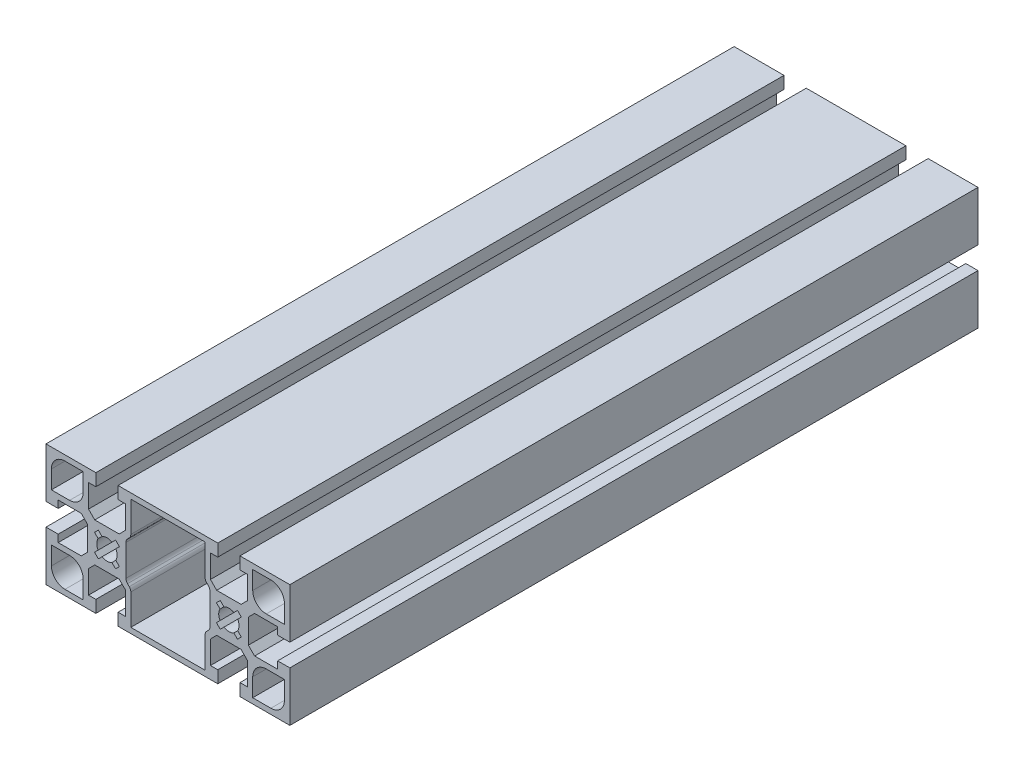
SolidWorks part; units mm, degrees
ref_plane "Front Plane" through (0, 0, 0) normal (0, 0, 1) x (1, 0, 0)
ref_plane "Top Plane" through (0, 0, 0) normal (0, 1, 0) x (1, 0, 0)
ref_plane "Right Plane" through (0, 0, 0) normal (1, 0, 0) x (0, 0, -1)
ref_plane "Plane1" through (0, 0, 0) normal (0, 0, -1) x (-1, 0, 0)
sketch "Sketch1" plane through (0, 0, 0) normal (0, 0, -1) x (-1, 0, 0)
  line L0 (14.9142, -7.1574) -> (14.2858, -7.7858)
  line L1 (13.7, -9.2) -> (13.7, -20.5)
  line L2 (13.7, -20.5) -> (-13.7, -20.5)
  line L3 (-13.7, -20.5) -> (-13.7, -9.2)
  line L4 (-14.2858, -7.7858) -> (-14.9142, -7.1574)
  line L5 (-15.5, -5.7432) -> (-15.5, 5.7432)
  line L6 (-14.9142, 7.1574) -> (-14.2858, 7.7858)
  line L7 (-13.7, 9.2) -> (-13.7, 20.5)
  line L8 (-13.7, 20.5) -> (13.7, 20.5)
  line L9 (13.7, 20.5) -> (13.7, 9.2)
  line L10 (14.2858, 7.7858) -> (14.9142, 7.1574)
  line L11 (15.5, 5.7432) -> (15.5, -5.7432)
  line L12 (43, 15.5) -> (43, 8.8)
  line L13 (43, 8.8) -> (36.3, 8.8)
  line L14 (31.3, 13.8) -> (31.3, 20.5)
  line L15 (31.3, 20.5) -> (38, 20.5)
  line L16 (-36.3, 8.8) -> (-43, 8.8)
  line L17 (-43, 8.8) -> (-43, 15.5)
  line L18 (-38, 20.5) -> (-31.3, 20.5)
  line L19 (-31.3, 20.5) -> (-31.3, 13.8)
  line L20 (-43, -15.5) -> (-43, -8.8)
  line L21 (-43, -8.8) -> (-36.3, -8.8)
  line L22 (-31.3, -13.8) -> (-31.3, -20.5)
  line L23 (-31.3, -20.5) -> (-38, -20.5)
  line L24 (36.3, -8.8) -> (43, -8.8)
  line L25 (43, -8.8) -> (43, -15.5)
  line L26 (38, -20.5) -> (31.3, -20.5)
  line L27 (31.3, -20.5) -> (31.3, -13.8)
  line L28 (-20.6515, 3.2627) -> (-19.318, 4.5962)
  line L29 (-19.318, 4.5962) -> (-17.9038, 3.182)
  line L30 (-17.9038, 3.182) -> (-19.2373, 1.8485)
  line L31 (-19.2373, -1.8485) -> (-17.9038, -3.182)
  line L32 (-17.9038, -3.182) -> (-19.318, -4.5962)
  line L33 (-19.318, -4.5962) -> (-20.6515, -3.2627)
  line L34 (-24.3485, -3.2627) -> (-25.682, -4.5962)
  line L35 (-25.682, -4.5962) -> (-27.0962, -3.182)
  line L36 (-27.0962, -3.182) -> (-25.7627, -1.8485)
  line L37 (-25.7627, 1.8485) -> (-27.0962, 3.182)
  line L38 (-27.0962, 3.182) -> (-25.682, 4.5962)
  line L39 (-25.682, 4.5962) -> (-24.3485, 3.2627)
  line L40 (27.0962, 3.182) -> (25.7627, 1.8485)
  line L41 (25.7627, -1.8485) -> (27.0962, -3.182)
  line L42 (27.0962, -3.182) -> (25.682, -4.5962)
  line L43 (25.682, -4.5962) -> (24.3485, -3.2627)
  line L44 (20.6515, -3.2627) -> (19.318, -4.5962)
  line L45 (19.318, -4.5962) -> (17.9038, -3.182)
  line L46 (17.9038, -3.182) -> (19.2373, -1.8485)
  line L47 (19.2373, 1.8485) -> (17.9038, 3.182)
  line L48 (17.9038, 3.182) -> (19.318, 4.5962)
  line L49 (19.318, 4.5962) -> (20.6515, 3.2627)
  line L50 (24.3485, 3.2627) -> (25.682, 4.5962)
  line L51 (25.682, 4.5962) -> (27.0962, 3.182)
  line L52 (-26.6, 22.5) -> (-45, 22.5)
  line L53 (-45, 22.5) -> (-45, 4.1)
  line L54 (-45, 4.1) -> (-40.5, 4.1)
  line L55 (-40.5, 4.1) -> (-40.5, 6.8)
  line L56 (-40.5, 6.8) -> (-32, 6.8)
  line L57 (-32, 6.8) -> (-29.7, 4.5)
  line L58 (-29.7, 4.5) -> (-29.7, -4.5)
  line L59 (-29.7, -4.5) -> (-32, -6.8)
  line L60 (-32, -6.8) -> (-40.5, -6.8)
  line L61 (-40.5, -6.8) -> (-40.5, -4.1)
  line L62 (-40.5, -4.1) -> (-45, -4.1)
  line L63 (-45, -4.1) -> (-45, -22.5)
  line L64 (-45, -22.5) -> (-26.6, -22.5)
  line L65 (-26.6, -22.5) -> (-26.6, -18)
  line L66 (-26.6, -18) -> (-29.3, -18)
  line L67 (-29.3, -18) -> (-29.3, -9.5)
  line L68 (-29.3, -9.5) -> (-27, -7.2)
  line L69 (-27, -7.2) -> (-18, -7.2)
  line L70 (-18, -7.2) -> (-15.7, -9.5)
  line L71 (-15.7, -9.5) -> (-15.7, -18)
  line L72 (-15.7, -18) -> (-18.4, -18)
  line L73 (-18.4, -18) -> (-18.4, -22.5)
  line L74 (-18.4, -22.5) -> (18.4, -22.5)
  line L75 (18.4, -22.5) -> (18.4, -18)
  line L76 (18.4, -18) -> (15.7, -18)
  line L77 (15.7, -18) -> (15.7, -9.5)
  line L78 (15.7, -9.5) -> (18, -7.2)
  line L79 (18, -7.2) -> (27, -7.2)
  line L80 (27, -7.2) -> (29.3, -9.5)
  line L81 (29.3, -9.5) -> (29.3, -18)
  line L82 (29.3, -18) -> (26.6, -18)
  line L83 (26.6, -18) -> (26.6, -22.5)
  line L84 (26.6, -22.5) -> (45, -22.5)
  line L85 (45, -22.5) -> (45, -4.1)
  line L86 (45, -4.1) -> (40.5, -4.1)
  line L87 (40.5, -4.1) -> (40.5, -6.8)
  line L88 (40.5, -6.8) -> (32, -6.8)
  line L89 (32, -6.8) -> (29.7, -4.5)
  line L90 (29.7, -4.5) -> (29.7, 4.5)
  line L91 (29.7, 4.5) -> (32, 6.8)
  line L92 (32, 6.8) -> (40.5, 6.8)
  line L93 (40.5, 6.8) -> (40.5, 4.1)
  line L94 (40.5, 4.1) -> (45, 4.1)
  line L95 (45, 4.1) -> (45, 22.5)
  line L96 (45, 22.5) -> (26.6, 22.5)
  line L97 (26.6, 22.5) -> (26.6, 18)
  line L98 (26.6, 18) -> (29.3, 18)
  line L99 (29.3, 18) -> (29.3, 9.5)
  line L100 (29.3, 9.5) -> (27, 7.2)
  line L101 (27, 7.2) -> (18, 7.2)
  line L102 (18, 7.2) -> (15.7, 9.5)
  line L103 (15.7, 9.5) -> (15.7, 18)
  line L104 (15.7, 18) -> (18.4, 18)
  line L105 (18.4, 18) -> (18.4, 22.5)
  line L106 (18.4, 22.5) -> (-18.4, 22.5)
  line L107 (-18.4, 22.5) -> (-18.4, 18)
  line L108 (-18.4, 18) -> (-15.7, 18)
  line L109 (-15.7, 18) -> (-15.7, 9.5)
  line L110 (-15.7, 9.5) -> (-18, 7.2)
  line L111 (-18, 7.2) -> (-27, 7.2)
  line L112 (-27, 7.2) -> (-29.3, 9.5)
  line L113 (-29.3, 9.5) -> (-29.3, 18)
  line L114 (-29.3, 18) -> (-26.6, 18)
  line L115 (-26.6, 18) -> (-26.6, 22.5)
  arc A0 (14.2858, -7.7858) -> (13.7, -9.2) centre (15.7, -9.2) ccw
  arc A1 (-13.7, -9.2) -> (-14.2858, -7.7858) centre (-15.7, -9.2) ccw
  arc A2 (-14.9142, -7.1574) -> (-15.5, -5.7432) centre (-13.5, -5.7432) cw
  arc A3 (-15.5, 5.7432) -> (-14.9142, 7.1574) centre (-13.5, 5.7432) cw
  arc A4 (-14.2858, 7.7858) -> (-13.7, 9.2) centre (-15.7, 9.2) ccw
  arc A5 (13.7, 9.2) -> (14.2858, 7.7858) centre (15.7, 9.2) ccw
  arc A6 (14.9142, 7.1574) -> (15.5, 5.7432) centre (13.5, 5.7432) cw
  arc A7 (15.5, -5.7432) -> (14.9142, -7.1574) centre (13.5, -5.7432) cw
  arc A8 (38, 20.5) -> (43, 15.5) centre (38, 15.5) cw
  arc A9 (36.3, 8.8) -> (31.3, 13.8) centre (36.3, 13.8) cw
  arc A10 (-43, 15.5) -> (-38, 20.5) centre (-38, 15.5) cw
  arc A11 (-31.3, 13.8) -> (-36.3, 8.8) centre (-36.3, 13.8) cw
  arc A12 (-38, -20.5) -> (-43, -15.5) centre (-38, -15.5) cw
  arc A13 (-36.3, -8.8) -> (-31.3, -13.8) centre (-36.3, -13.8) cw
  arc A14 (43, -15.5) -> (38, -20.5) centre (38, -15.5) cw
  arc A15 (31.3, -13.8) -> (36.3, -8.8) centre (36.3, -13.8) cw
  arc A16 (-24.3485, 3.2627) -> (-20.6515, 3.2627) centre (-22.5, 0) cw
  arc A17 (-19.2373, 1.8485) -> (-19.2373, -1.8485) centre (-22.5, 0) cw
  arc A18 (-20.6515, -3.2627) -> (-24.3485, -3.2627) centre (-22.5, 0) cw
  arc A19 (-25.7627, -1.8485) -> (-25.7627, 1.8485) centre (-22.5, 0) cw
  arc A20 (25.7627, 1.8485) -> (25.7627, -1.8485) centre (22.5, 0) cw
  arc A21 (24.3485, -3.2627) -> (20.6515, -3.2627) centre (22.5, 0) cw
  arc A22 (19.2373, -1.8485) -> (19.2373, 1.8485) centre (22.5, 0) cw
  arc A23 (20.6515, 3.2627) -> (24.3485, 3.2627) centre (22.5, 0) cw
extrude "Boss-Extrude1" add sketch "Sketch1" against normal blind 254
